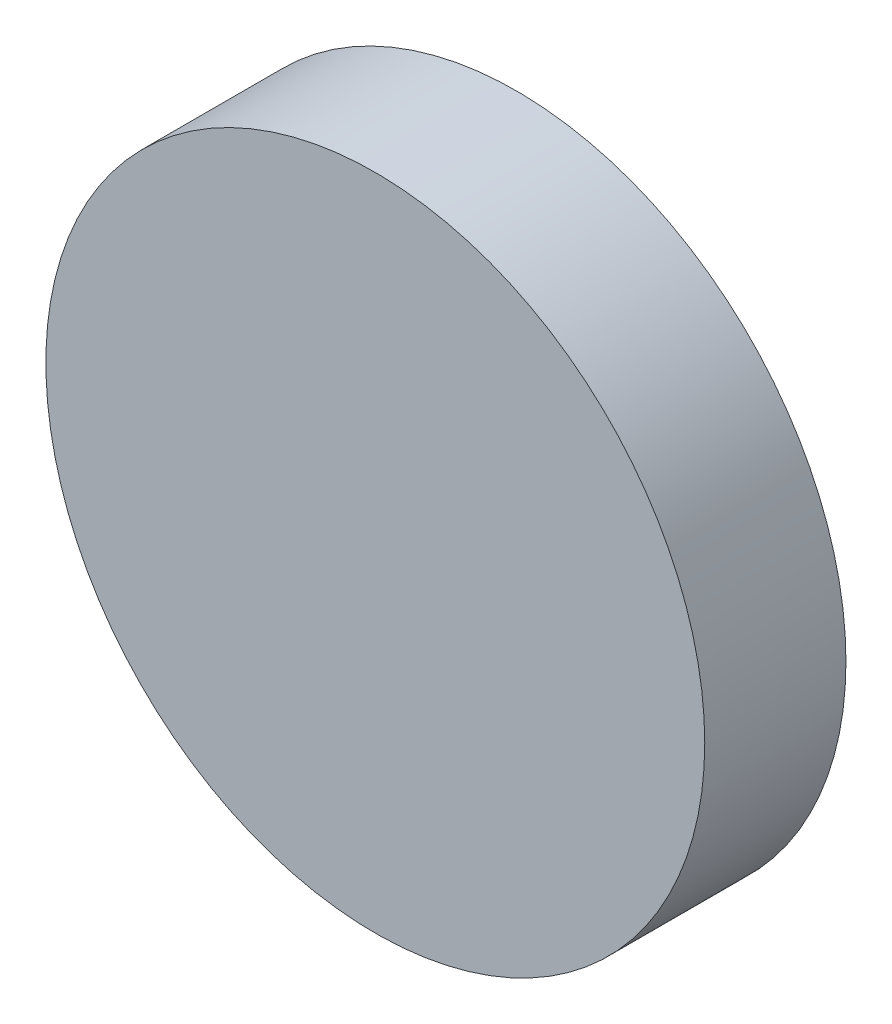
SolidWorks part; units mm, degrees
ref_plane "Front Plane" through (0, 0, 0) normal (0, 0, 1) x (1, 0, 0)
ref_plane "Top Plane" through (0, 0, 0) normal (0, 1, 0) x (1, 0, 0)
ref_plane "Right Plane" through (0, 0, 0) normal (1, 0, 0) x (0, 0, -1)
sketch "Sketch1" plane through (0, 0, 0) normal (0, 0, 1) x (1, 0, 0)
  circle A0 centre (0, 0) radius 3.5
  dimension "D1" = 7
extrude "Boss-Extrude1" add sketch "Sketch1" along normal blind 1.5
